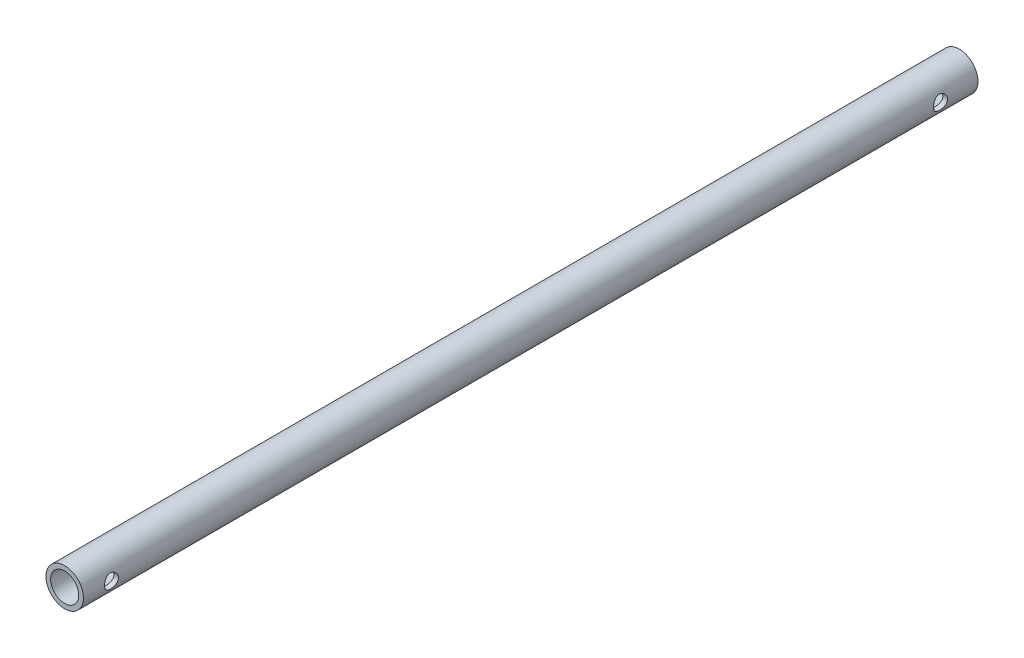
SolidWorks part; units mm, degrees
ref_plane "Płaszczyzna przednia" through (0, 0, 0) normal (0, 0, 1) x (1, 0, 0)
ref_plane "Płaszczyzna górna" through (0, 0, 0) normal (0, 1, 0) x (1, 0, 0)
ref_plane "Płaszczyzna prawa" through (0, 0, 0) normal (1, 0, 0) x (0, 0, -1)
sketch "Sketch1" plane through (0, 0, 0) normal (0, 0, 1) x (1, 0, 0)
  circle A0 centre (0, 0) radius 4
  circle A1 centre (0, 0) radius 3
  dimension "D1" = 8
  dimension "D2" = 6
extrude "Boss-Extrude1" add sketch "Sketch1" along normal blind 191
ref_plane "Plane1" through (4, 0, 0) normal (1, 0, 0) x (0, 0, -1)
sketch "Sketch3" plane through (4, 0, 0) normal (1, 0, 0) x (0, 0, -1)
  line L0 (-191, 4) -> (-191, -4) construction
  line L1 (0, -4) -> (0, 4) construction
  line L2 (-191, 0) -> (0, 0) construction
  circle A0 centre (-185, 0) radius 1.5
  circle A1 centre (-8, 0) radius 1.5
  point P8 (-8, -0.2066)
  point P9 (0, 0)
  point P14 (-184.98, -0.7723)
  dimension "D2" = 3
  dimension "D3" = 3
  dimension "D1" = 6
  dimension "D4" = 8
extrude "Cut-Extrude1" cut sketch "Sketch3" against normal through all and the other way through all
